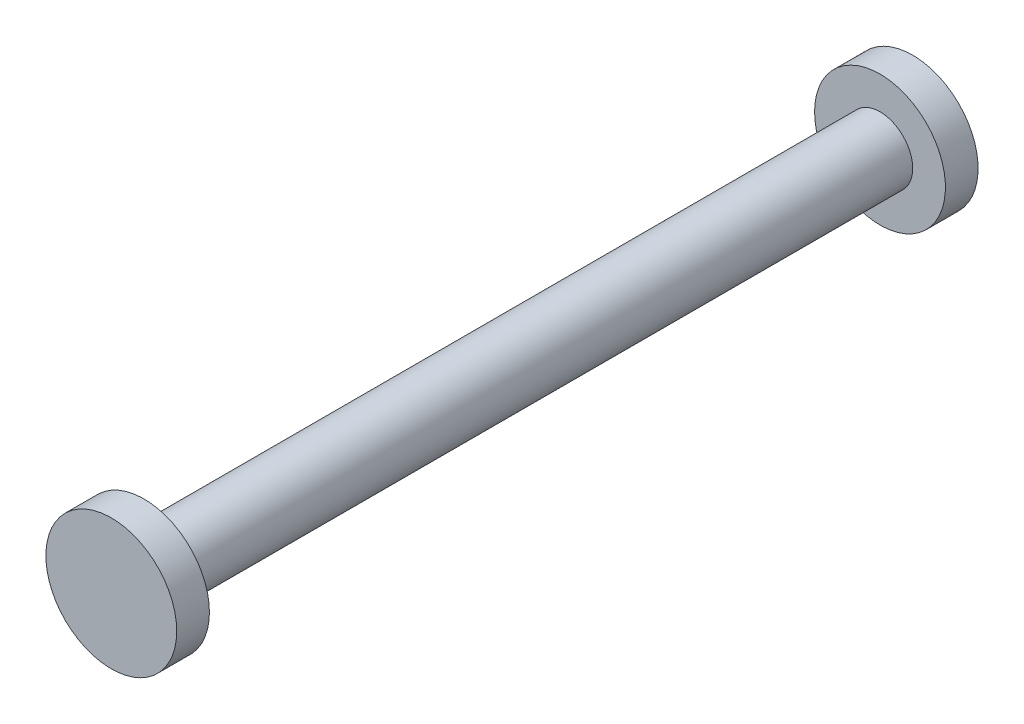
SolidWorks part; units mm, degrees
material "Cast Alloy Steel"
ref_plane "Front Plane" through (0, 0, 0) normal (0, 0, 1) x (1, 0, 0)
ref_plane "Top Plane" through (0, 0, 0) normal (0, 1, 0) x (1, 0, 0)
ref_plane "Right Plane" through (0, 0, 0) normal (1, 0, 0) x (0, 0, -1)
sketch "Sketch1" plane through (0, 0, 0) normal (0, 0, 1) x (1, 0, 0)
  circle A0 centre (0, 0) radius 2.54
  dimension "D1" = 5.08
extrude "Boss-Extrude1" add sketch "Sketch1" along normal blind 57.15
sketch "Sketch2" plane through (0, 0, 57.15) normal (0, 0, 1) x (1, 0, 0)
  circle A0 centre (0, 0) radius 5.08
  dimension "D2" = 10.16
extrude "Boss-Extrude2" add sketch "Sketch2" along normal blind 2.54
sketch "Sketch3" plane through (0, 0, 0) normal (0, 0, -1) x (-1, 0, 0)
  circle A0 centre (0, 0) radius 5.08
  dimension "D2" = 10.16
extrude "Boss-Extrude3" add sketch "Sketch3" along normal blind 2.54
